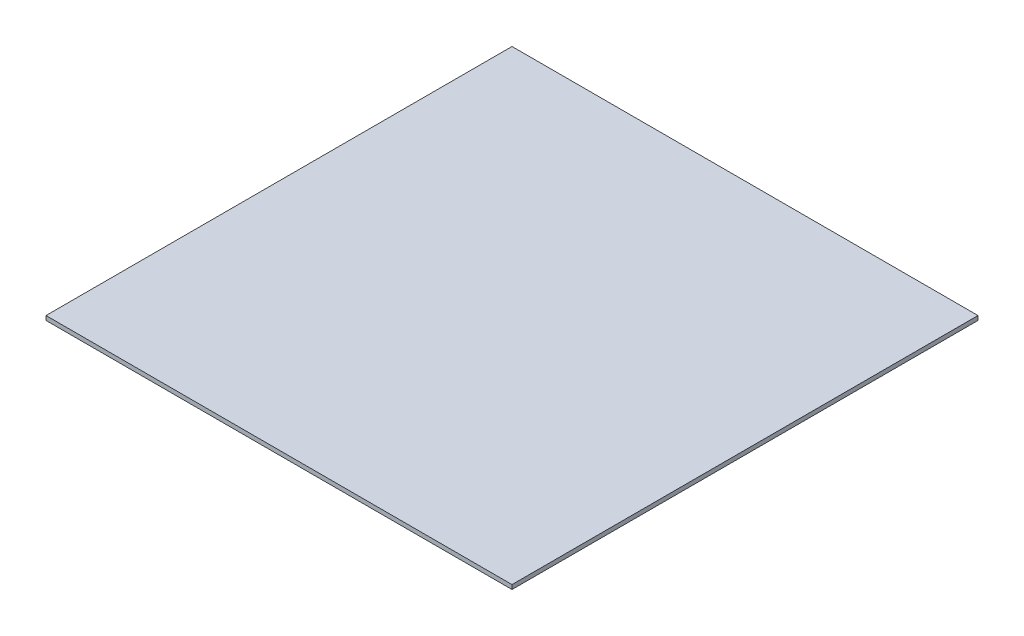
SolidWorks part; units mm, degrees
ref_plane "Front Plane" through (0, 0, 0) normal (0, 0, 1) x (1, 0, 0)
ref_plane "Top Plane" through (0, 0, 0) normal (0, 1, 0) x (1, 0, 0)
ref_plane "Right Plane" through (0, 0, 0) normal (1, 0, 0) x (0, 0, -1)
sketch "Sketch1" plane through (0, 0, 0) normal (0, 1, 0) x (1, 0, 0)
  line L1 (-163, 163) -> (163, 163)
  line L2 (-163, 163) -> (-163, -163)
  line L3 (-163, -163) -> (163, -163)
  line L4 (163, 163) -> (163, -163)
  line L5 (-163, 163) -> (163, -163) construction
  line L6 (-163, -163) -> (163, 163) construction
  point P0 (0, 0)
  dimension "D1" = 326
  dimension "D2" = 326
extrude "Boss-Extrude1" add sketch "Sketch1" along normal blind 3
